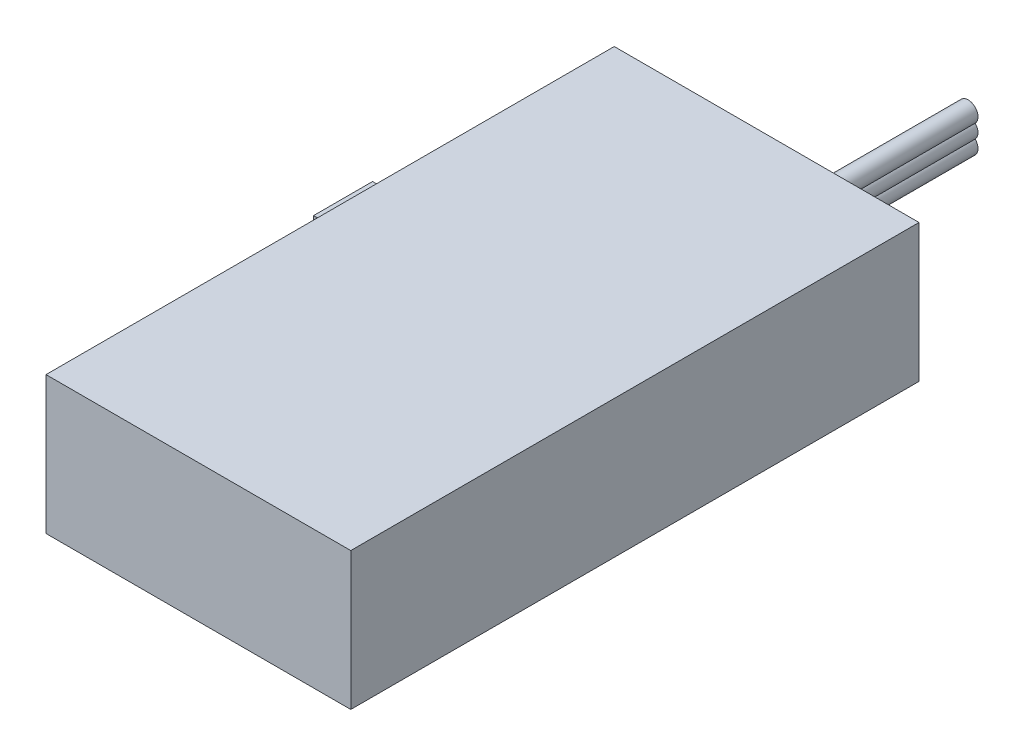
SolidWorks part; units mm, degrees
ref_plane "Plan de face" through (0, 0, 0) normal (0, 0, 1) x (1, 0, 0)
ref_plane "Plan de dessus" through (0, 0, 0) normal (0, 1, 0) x (1, 0, 0)
ref_plane "Plan de droite" through (0, 0, 0) normal (1, 0, 0) x (0, 0, -1)
sketch "Esquisse1" plane through (0, 0, 0) normal (0, 1, 0) x (1, 0, 0)
  line L1 (0, 0) -> (15.5, 0)
  line L2 (0, 0) -> (0, -28.9)
  line L3 (0, -28.9) -> (15.5, -28.9)
  line L4 (15.5, 0) -> (15.5, -28.9)
  dimension "D1" = 15.5
  dimension "L" = 28.9
extrude "Boss.-Extru.1" add sketch "Esquisse1" along normal blind 7
sketch "Esquisse2" plane through (0, 0, 0) normal (-1, 0, 0) x (0, 0, 1)
  line L0 (28.9, 7) -> (28.9, 0) construction
  line L1 (2.3, 4.7) -> (22.9, 4.7)
  line L2 (2.3, 4.7) -> (2.3, 2.3)
  line L3 (2.3, 2.3) -> (22.9, 2.3)
  line L4 (22.9, 4.7) -> (22.9, 2.3)
  line L5 (0, 7) -> (0, 0) construction
  line L6 (0, 7) -> (28.9, 7) construction
  line L7 (0, 0) -> (28.9, 0) construction
  point P6 (4.3313, 5.2413)
  dimension "D1" = 6
  dimension "D2" = 2.3
  dimension "D3" = 2.3
  dimension "D4" = 2.3
extrude "Enlèv. mat.-Extru.1" cut sketch "Esquisse2" against normal blind 8
sketch "Esquisse3" plane through (0, 0, 2.3) normal (0, 0, 1) x (1, 0, 0)
  line L0 (8, 2.3) -> (0, 2.3) construction
  line L3 (0, 4.7) -> (0, 2.3) construction
  circle A0 centre (3.4, 3.5) radius 0.4
  dimension "D1" = 0.8
  dimension "D2" = 1.2
  dimension "D3" = 3.4
extrude "Boss.-Extru.2" add sketch "Esquisse3" along normal up to next
ref_plane "Plan1" through (3, 0, 0) normal (-1, 0, 0) x (0, 0, 1)
sketch "Esquisse4" plane through (3, 0, 0) normal (-1, 0, 0) x (0, 0, 1)
  line L0 (22.9, 4.7) -> (2.3, 4.7) construction
  line L1 (9.792, 4.7) -> (12.792, 4.7)
  line L2 (9.792, 4.7) -> (9.792, 2.3)
  line L3 (9.792, 2.3) -> (12.792, 2.3)
  line L4 (12.792, 4.7) -> (12.792, 2.3)
  line L5 (2.3, 2.3) -> (22.9, 2.3) construction
  dimension "D1" = 3
extrude "Boss.-Extru.4" add sketch "Esquisse4" along normal blind 5.5 separate body
sketch "Esquisse6" plane through (0, 0, 0) normal (0, 0, -1) x (-1, 0, 0)
  line L0 (0, 7) -> (0, 0) construction
  line L1 (-9.5, 4.65) -> (-8.5, 4.65) construction
  line L2 (-9.5, 4.65) -> (-9.5, 2.25) construction
  line L3 (-9.5, 2.25) -> (-8.5, 2.25) construction
  line L4 (-8.5, 4.65) -> (-8.5, 2.25) construction
  line L5 (-9.5, 3.45) -> (-8.5, 3.45) construction
  line L6 (-15.5, 7) -> (0, 7) construction
  circle A0 centre (-9, 4.15) radius 0.5
  circle A1 centre (-9, 3.45) radius 0.5
  circle A2 centre (-9, 2.75) radius 0.5
  dimension "D1" = 2.4
  dimension "D2" = 1
  dimension "D3" = 8.5
  dimension "D4" = 2.35
  dimension "D5" = 1.2
extrude "Boss.-Extru.5" add sketch "Esquisse6" along normal blind 9 contours A2 | A1 | A0
equation "\"D3@Esquisse3\"=3.0+0.4"
